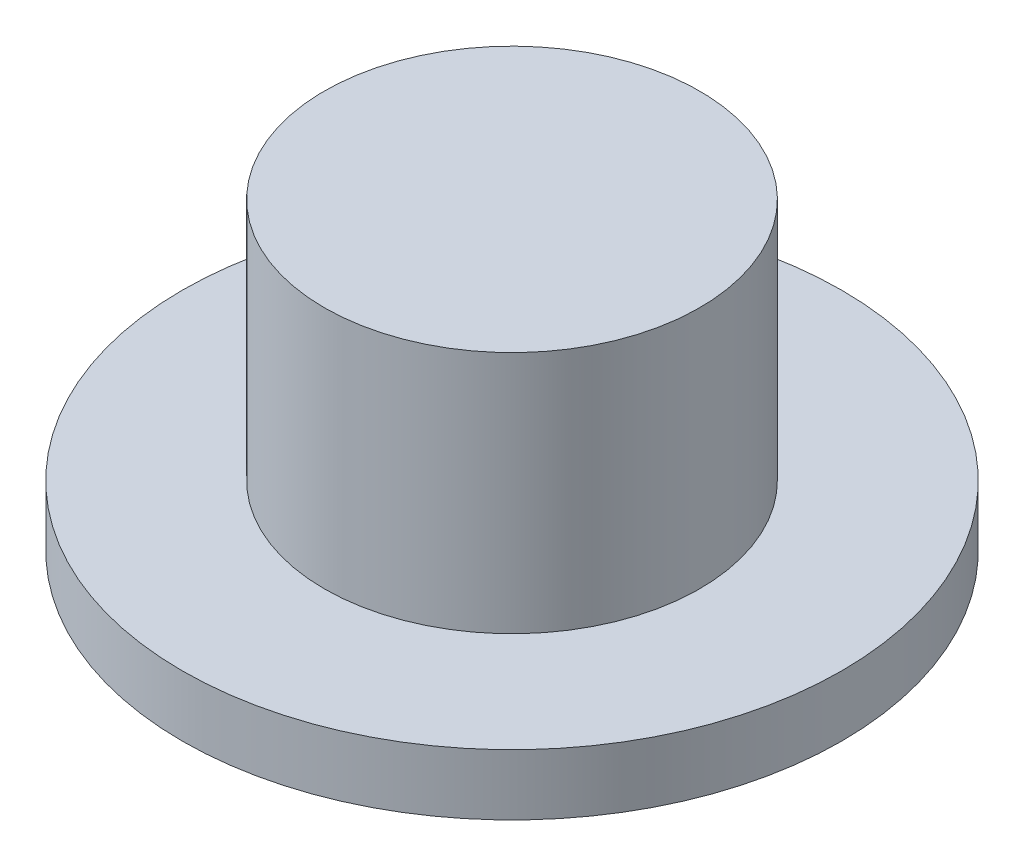
SolidWorks part; units mm, degrees
ref_plane "Front Plane" through (0, 0, 0) normal (0, 0, 1) x (1, 0, 0)
ref_plane "Top Plane" through (0, 0, 0) normal (0, 1, 0) x (1, 0, 0)
ref_plane "Right Plane" through (0, 0, 0) normal (1, 0, 0) x (0, 0, -1)
sketch "Sketch1" plane through (0, 0, 0) normal (0, 1, 0) x (1, 0, 0)
  circle A0 centre (0, 0) radius 6.5
extrude "Boss-Extrude1" add sketch "Sketch1" along normal blind 1.2
sketch "Sketch2" plane through (0, 1.2, 0) normal (0, 1, 0) x (1, 0, 0)
  circle A0 centre (0, 0) radius 3.7
extrude "Boss-Extrude2" add sketch "Sketch2" along normal blind 4.8
